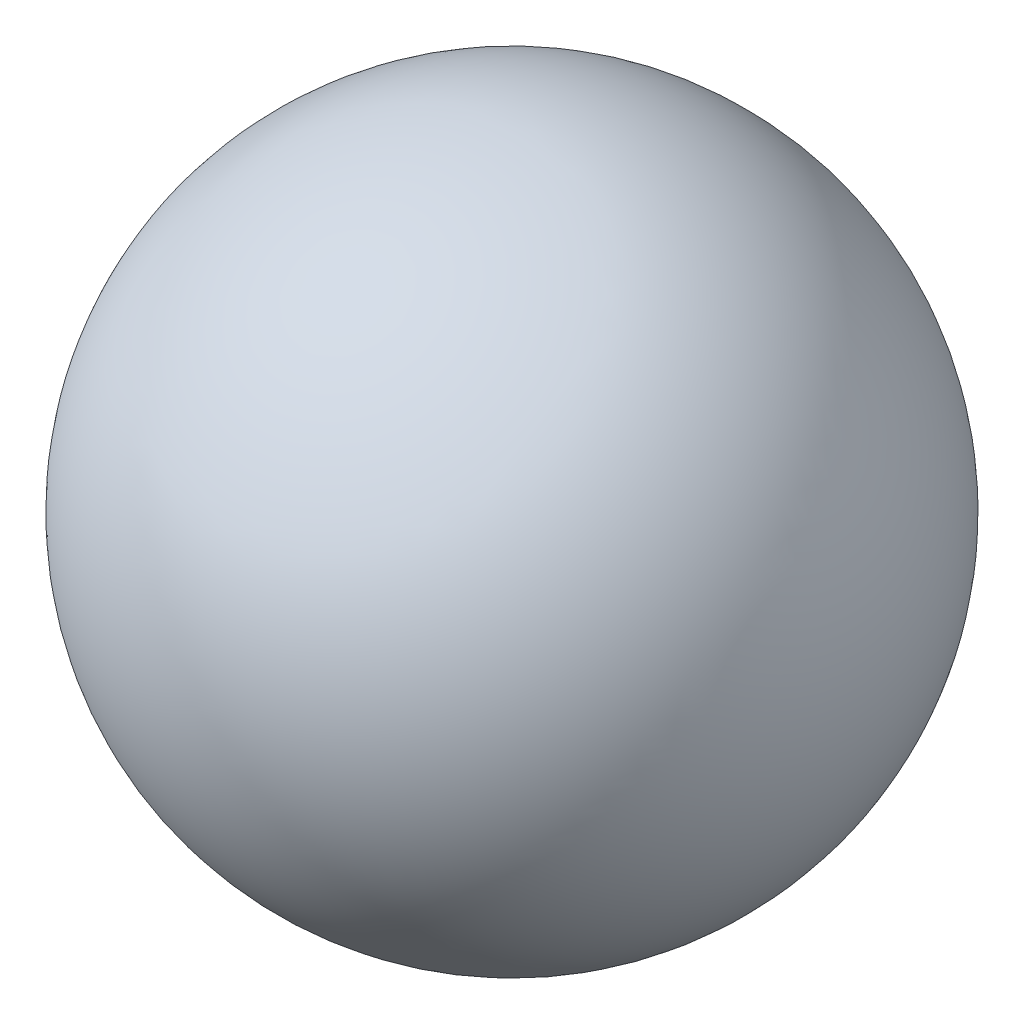
SolidWorks part; units mm, degrees
ref_plane "Front Plane" through (0, 0, 0) normal (0, 0, 1) x (1, 0, 0)
ref_plane "Top Plane" through (0, 0, 0) normal (0, 1, 0) x (1, 0, 0)
ref_plane "Right Plane" through (0, 0, 0) normal (1, 0, 0) x (0, 0, -1)
sketch "Sketch2" plane through (0, 0, 0) normal (0, 0, 1) x (1, 0, 0)
  line L0 (-88.9, 0) -> (88.9, 0)
  arc A0 (88.9, 0) -> (-88.9, 0) centre (0, 0) ccw
revolve "Revolve1" add sketch "Sketch2" angle 360 about L0
